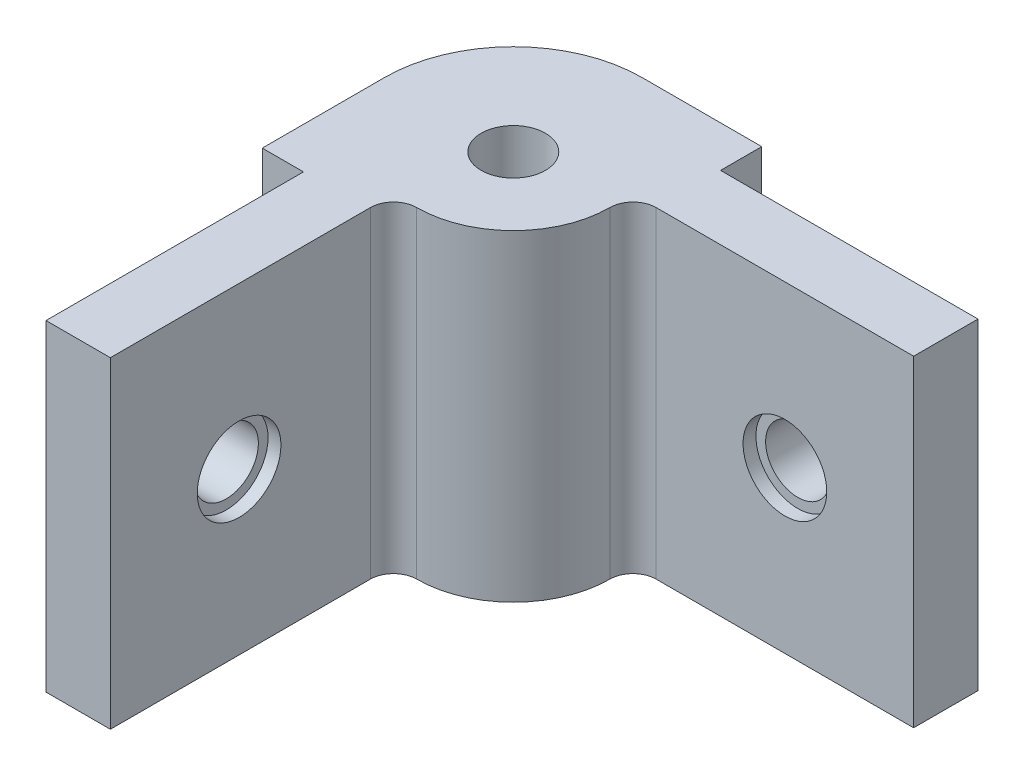
SolidWorks part; units mm, degrees
material "ABS"
ref_plane "Front Plane" through (0, 0, 0) normal (0, 0, 1) x (1, 0, 0)
ref_plane "Top Plane" through (0, 0, 0) normal (0, 1, 0) x (1, 0, 0)
ref_plane "Right Plane" through (0, 0, 0) normal (1, 0, 0) x (0, 0, -1)
sketch "Sketch4" plane through (0, 0, 0) normal (0, 1, 0) x (1, 0, 0)
  line L12 (12.8597, 14.3012) -> (32.8597, 14.3012)
  line L18 (3.5597, 22.5012) -> (3.5597, 12.5012) construction
  line L19 (12.8597, 12.5012) -> (11.0597, 12.5012) construction
  line L20 (-6.4403, 12.5012) -> (-6.4403, 3.0012)
  line L27 (12.8597, 14.3012) -> (12.8597, 12.5012) construction
  line L28 (3.5597, 5.0012) -> (3.5597, 3.2012) construction
  line L29 (3.5597, 3.2012) -> (1.7597, 3.2012) construction
  line L35 (1.7597, 3.2012) -> (1.7597, -16.9988)
  line L40 (3.5597, 12.5012) -> (-6.4403, 12.5012) construction
  line L42 (11.0597, 12.5012) -> (3.5597, 12.5012) construction
  line L44 (-6.4403, 3.0012) -> (-3.2403, 3.0012)
  line L45 (-3.2403, 3.0012) -> (-3.2403, -16.9988)
  line L46 (-3.2403, -16.9988) -> (1.7597, -16.9988)
  line L47 (3.5597, 12.5012) -> (3.5597, 5.0012) construction
  line L50 (3.5597, 22.5012) -> (12.8597, 22.5012)
  line L51 (12.8597, 22.5012) -> (12.8597, 19.3012)
  line L52 (12.8597, 19.3012) -> (32.8597, 19.3012)
  line L53 (32.8597, 19.3012) -> (32.8597, 14.3012)
  line L55 (5.3274, 10.7334) -> (8.863, 7.1979) construction
  line L56 (5.3274, 10.7334) -> (3.5597, 12.5012) construction
  arc A2 (3.5597, 22.5012) -> (-6.4403, 12.5012) centre (3.5597, 12.5012) ccw
  arc A6 (3.5597, 5.0012) -> (1.7597, 3.2012) centre (3.5597, 3.2012) ccw
  arc A7 (11.0597, 12.5012) -> (12.8597, 14.3012) centre (12.8597, 12.5012) cw
  circle A14 centre (3.5597, 12.5012) radius 2.5
  arc A17 (11.0597, 12.5012) -> (3.5597, 5.0012) centre (3.5597, 12.5012) cw
extrude "Boss-Extrude1" add sketch "Sketch4" along normal blind 25
sketch "Sketch5" plane through (0, 0, -19.3012) normal (0, 0, -1) x (-1, 0, 0)
  line L0 (-12.8597, 25) -> (-32.8597, 25) construction
  line L1 (-22.8597, 25) -> (-22.8597, 0) construction
  line L2 (-32.8597, 0) -> (-12.8597, 0) construction
  circle A0 centre (-22.8597, 12.5) radius 2.5
  point P2 (-22.8597, 25)
  point P9 (-22.8597, 12.5)
  dimension "D1" = 5
extrude "Cut-Extrude1" cut sketch "Sketch5" against normal through all
sketch "Sketch7" plane through (1.7597, 0, 0) normal (1, 0, 0) x (0, 0, -1)
  line L0 (-16.9988, 25) -> (3.0012, 25) construction
  line L1 (-6.9988, 25) -> (-6.9988, 0) construction
  line L2 (3.0012, 0) -> (-16.9988, 0) construction
  circle A0 centre (-6.9988, 12.5) radius 2.5
  point P2 (-6.9988, 25)
  point P9 (-6.9988, 12.5)
  dimension "D1" = 5
extrude "Cut-Extrude3" cut sketch "Sketch7" against normal through all and the other way through all
sketch "Sketch8" plane through (1.7597, 0, 0) normal (1, 0, 0) x (0, 0, -1)
  circle A0 centre (-6.9988, 12.5) radius 3.25
  dimension "D1" = 6.5
extrude "Cut-Extrude4" cut sketch "Sketch8" against normal blind 1
sketch "Sketch6" plane through (0, 0, -14.3012) normal (0, 0, 1) x (1, 0, 0)
  circle A0 centre (22.8597, 12.5) radius 3.25
  circle A1 centre (22.8597, 12.5) radius 2.5 construction
  dimension "D1" = 6.5
extrude "Cut-Extrude2" cut sketch "Sketch6" against normal blind 1
equation "\"tolerance\"= 0.1mm"
